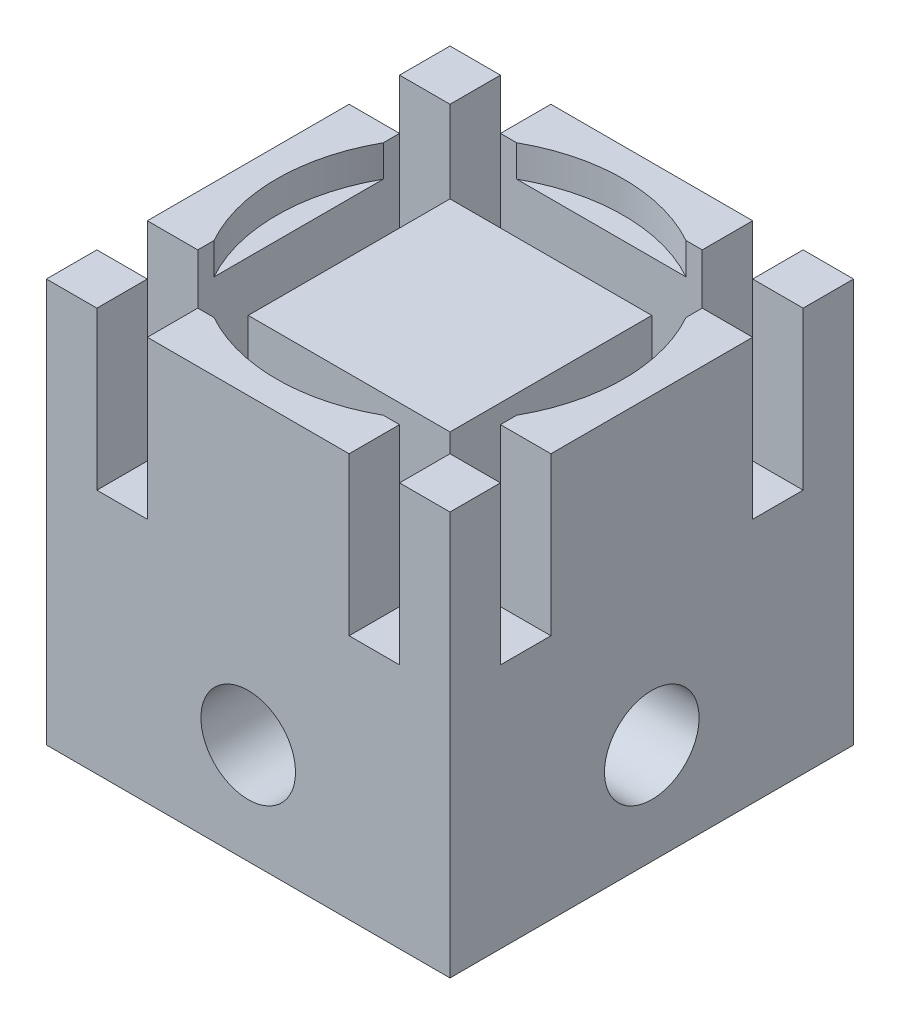
SolidWorks part; units mm, degrees
ref_plane "Front Plane" through (0, 0, 0) normal (0, 0, 1) x (1, 0, 0)
ref_plane "Top Plane" through (0, 0, 0) normal (0, 1, 0) x (1, 0, 0)
ref_plane "Right Plane" through (0, 0, 0) normal (1, 0, 0) x (0, 0, -1)
ref_plane "Plane1" through (0, 0, -16.256) normal (0, 0, 1) x (1, 0, 0)
sketch "Sketch2" plane through (0, 0, 0) normal (0, 0, 1) x (1, 0, 0)
  line L1 (-8.128, 12.7) -> (8.128, 12.7)
  line L2 (-8.128, 12.7) -> (-8.128, -3.556)
  line L3 (-8.128, -3.556) -> (8.128, -3.556)
  line L4 (8.128, 12.7) -> (8.128, -3.556)
  dimension "D1" = 16.256
  dimension "D2" = 16.256
  dimension "D3" = 8.128
  dimension "D4" = 12.7
extrude "Boss-Extrude1" add sketch "Sketch2" against normal blind 16.256
ref_plane "Plane2" through (0, 0, -8.128) normal (0, 0, 1) x (1, 0, 0)
sketch "Sketch3" plane through (0, 12.7, 0) normal (0, 1, 0) x (1, 0, 0)
  circle A0 centre (0, 8.128) radius 6.985
  dimension "D3" = 13.97
  dimension "D1" = 8.128
  dimension "D2" = 0
extrude "Cut-Extrude1" cut sketch "Sketch3" against normal blind 1.27
sketch "Sketch4" plane through (0, 12.7, 0) normal (0, 1, 0) x (1, 0, 0)
  line L0 (-8.128, 16.256) -> (-8.128, 0) construction
  line L1 (-6.096, 16.256) -> (-4.064, 16.256)
  line L2 (-6.096, 16.256) -> (-6.096, 0)
  line L3 (-6.096, 0) -> (-4.064, 0)
  line L4 (-4.064, 16.256) -> (-4.064, 0)
  line L5 (4.064, 16.256) -> (6.096, 16.256)
  line L6 (4.064, 16.256) -> (4.064, 0)
  line L7 (4.064, 0) -> (6.096, 0)
  line L8 (6.096, 16.256) -> (6.096, 0)
  line L9 (8.128, 14.224) -> (-8.128, 14.224)
  line L10 (8.128, 14.224) -> (8.128, 12.192)
  line L11 (8.128, 12.192) -> (-8.128, 12.192)
  line L12 (-8.128, 14.224) -> (-8.128, 12.192)
  line L13 (-8.128, 4.064) -> (8.128, 4.064)
  line L14 (-8.128, 4.064) -> (-8.128, 2.032)
  line L15 (-8.128, 2.032) -> (8.128, 2.032)
  line L16 (8.128, 4.064) -> (8.128, 2.032)
  line L17 (8.128, 16.256) -> (8.128, 0) construction
  line L18 (8.128, 16.256) -> (-8.128, 16.256) construction
  line L19 (8.128, 0) -> (-8.128, 0) construction
  dimension "D1" = 2.032
  dimension "D2" = 4.064
  dimension "D3" = 8.128
  dimension "D4" = 8.128
  dimension "D5" = 4.064
extrude "Cut-Extrude3" cut sketch "Sketch4" against normal blind 6.35 contours L2 L3 L4 L1 | L13 L16 L15 L14 | L9 L12 L11 L10 | L6 L7 L8 L5
sketch "Sketch7" plane through (0, 0, 0) normal (0, 0, 1) x (1, 0, 0)
  line L0 (-8.128, -3.556) -> (8.128, -3.556) construction
  line L1 (8.128, -3.556) -> (8.128, 12.7) construction
  circle A0 centre (0, 0.508) radius 1.905
  dimension "D3" = 3.81
  dimension "D1" = 4.064
  dimension "D2" = 8.128
extrude "Cut-Extrude5" cut sketch "Sketch7" against normal through all
sketch "Sketch8" plane through (8.128, 0, 0) normal (1, 0, 0) x (0, 0, -1)
  line L0 (0, -3.556) -> (0, 12.7) construction
  line L1 (16.256, -3.556) -> (0, -3.556) construction
  circle A0 centre (8.128, 0.508) radius 1.905
  dimension "D3" = 3.81
  dimension "D1" = 8.128
  dimension "D2" = 4.064
extrude "Cut-Extrude6" cut sketch "Sketch8" against normal through all
